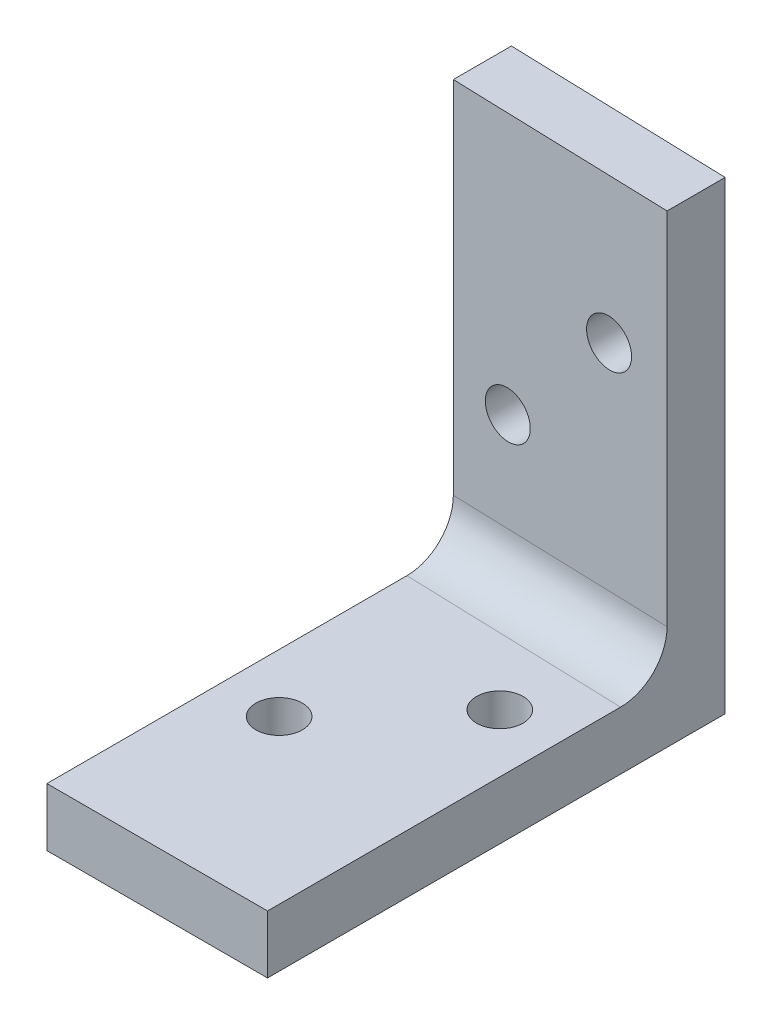
SolidWorks part; units mm, degrees
ref_plane "Front Plane" through (0, 0, 0) normal (0, 0, 1) x (1, 0, 0)
ref_plane "Top Plane" through (0, 0, 0) normal (0, 1, 0) x (1, 0, 0)
ref_plane "Right Plane" through (0, 0, 0) normal (1, 0, 0) x (0, 0, -1)
sketch "Sketch1" plane through (0, 0, 0) normal (0, 1, 0) x (1, 0, 0)
  line L1 (-9.5, -20) -> (9.5, -20)
  line L2 (-9.5, -20) -> (-9.5, 20)
  line L3 (-9.5, 20) -> (9.5, 20)
  line L4 (9.5, -20) -> (9.5, 20)
  line L5 (-9.5, -20) -> (9.5, 20) construction
  line L6 (-9.5, 20) -> (9.5, -20) construction
  point P0 (0, 0)
  dimension "D1" = 19
  dimension "D2" = 40
extrude "Boss-Extrude1" add sketch "Sketch1" along normal blind 5
sketch "Sketch2" plane through (0, 5, 0) normal (0, 1, 0) x (1, 0, 0)
  line L0 (-9.5, 20) -> (9.5, 19.4029)
  line L1 (9.5, -20) -> (9.5, 20) construction
  line L2 (9.5, 19.4029) -> (9.5, 20)
  line L3 (9.5, 20) -> (-9.5, 20)
  dimension "D1" = 1.8
extrude "Cut-Extrude1" cut sketch "Sketch2" against normal through all
sketch "Sketch3" plane through (0, 5, 0) normal (0, 1, 0) x (1, 0, 0)
  line L0 (-9.5, 20) -> (9.5, 19.4029)
  line L1 (9.5, 19.4029) -> (9.5, 14.4029)
  line L2 (9.5, -20) -> (9.5, 19.4029) construction
  line L3 (9.5, 14.4029) -> (-9.5, 15)
  line L4 (-9.5, 20) -> (-9.5, -20) construction
  line L5 (-9.5, 15) -> (-9.5, 20)
  dimension "D1" = 5
extrude "Boss-Extrude2" add sketch "Sketch3" along normal blind 35
sketch "Sketch4" plane through (0, 5, 0) normal (0, 1, 0) x (1, 0, 0)
  line L0 (9.5, -20) -> (9.5, 14.4029) construction
  line L1 (-9.5, 15) -> (-9.5, -20) construction
  line L3 (-9.5, -20) -> (9.5, -20) construction
  circle A0 centre (-4.5, -5) radius 2
  circle A1 centre (4.5, 5) radius 2
  dimension "D1" = 4
  dimension "D2" = 4
  dimension "D3" = 5
  dimension "D4" = 5
  dimension "D6" = 25
  dimension "D5" = 15
extrude "Cut-Extrude2" cut sketch "Sketch4" against normal through all
sketch "Sketch5" plane through (0.6185, 0, -19.682) normal (0.0314, 0, -0.9995) x (-0.9995, 0, -0.0314)
  line L0 (-8.8859, 40) -> (10.1235, 40) construction
  line L1 (-8.8859, 0) -> (-8.8859, 40) construction
  line L2 (10.1235, 40) -> (10.1235, 0) construction
  circle A0 centre (-3.8859, 27.5) radius 2
  circle A1 centre (5.1235, 17.5) radius 2
  dimension "D1" = 4
  dimension "D2" = 4
  dimension "D4" = 10
  dimension "D5" = 5
  dimension "D6" = 5
  dimension "D3" = 12.5
extrude "Cut-Extrude3" cut sketch "Sketch5" against normal through all
fillet "Fillet1" radius 4 1 edges at (0, 5, -14.7015)
